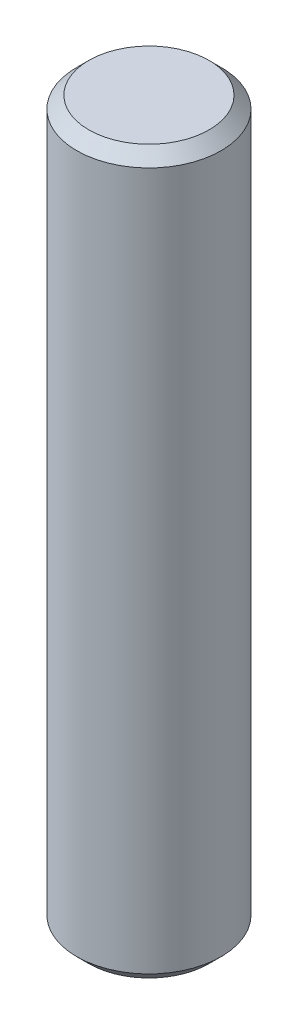
SolidWorks part; units mm, degrees
ref_plane "Front Plane" through (0, 0, 0) normal (0, 0, 1) x (1, 0, 0)
ref_plane "Top Plane" through (0, 0, 0) normal (0, 1, 0) x (1, 0, 0)
ref_plane "Right Plane" through (0, 0, 0) normal (1, 0, 0) x (0, 0, -1)
sketch "Sketch1" plane through (0, 0, 0) normal (0, 1, 0) x (1, 0, 0)
  circle A0 centre (0, 0) radius 3
  dimension "D1" = 6
extrude "Boss-Extrude1" add sketch "Sketch1" along normal blind 30
chamfer "Chamfer1" distance 0.5 angle 45 2 edges at (0, 0, 3) (0, 30, 3)
